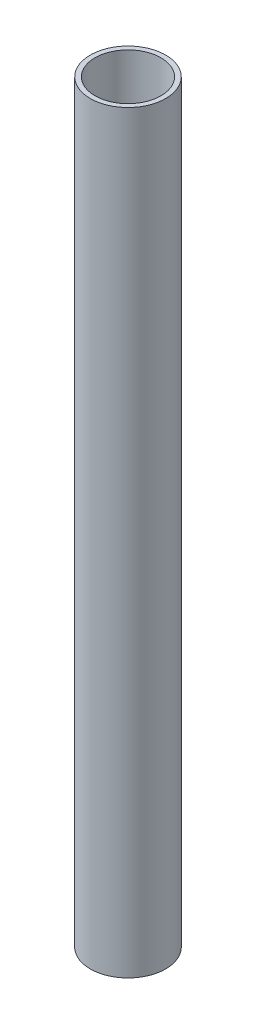
SolidWorks part; units mm, degrees
ref_plane "前视基准面" through (0, 0, 0) normal (0, 0, 1) x (1, 0, 0)
ref_plane "上视基准面" through (0, 0, 0) normal (0, 1, 0) x (1, 0, 0)
ref_plane "右视基准面" through (0, 0, 0) normal (1, 0, 0) x (0, 0, -1)
sketch "草图1" plane through (0, 0, 0) normal (0, 1, 0) x (1, 0, 0)
  circle A0 centre (0, 0) radius 7
  circle A1 centre (0, 0) radius 8
  dimension "D1" = 16
  dimension "D2" = 14
extrude "凸台-拉伸1" add sketch "草图1" along normal blind 160
